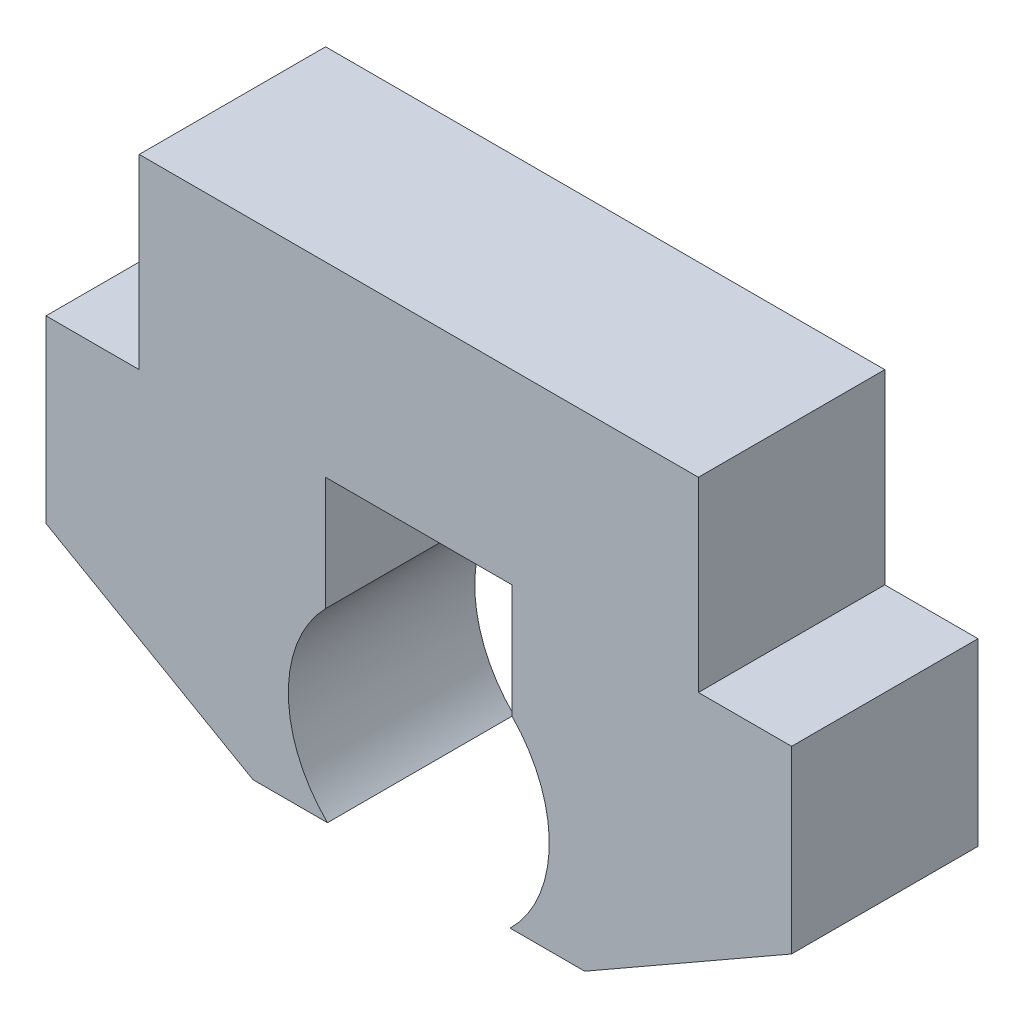
SolidWorks part; units mm, degrees
ref_plane "Спереди" through (0, 0, 0) normal (0, 0, 1) x (1, 0, 0)
ref_plane "Сверху" through (0, 0, 0) normal (0, 1, 0) x (1, 0, 0)
ref_plane "Справа" through (0, 0, 0) normal (1, 0, 0) x (0, 0, -1)
sketch "Sketch1" plane through (0, 0, 0) normal (0, 0, 1) x (1, 0, 0)
  line L0 (0, 8.8246) -> (20, 8.8246) construction
  line L1 (5.5505, 0.8246) -> (7.5505, 0.8246)
  line L2 (0, 4) -> (0, 8.8246)
  line L4 (20, 4) -> (20, 8.8246)
  line L5 (10, 0.8246) -> (10, 14.8323) construction
  line L6 (0, 4) -> (5.5505, 0.8246)
  line L7 (20, 4) -> (14.4495, 0.8246)
  line L8 (12.4495, 0.8246) -> (14.4495, 0.8246)
  line L9 (0, 4) -> (20, 4) construction
  line L12 (7.5, 8.8246) -> (12.5, 8.8246)
  line L14 (7.5, 8.8246) -> (7.5, 5.7741)
  line L15 (12.5, 8.8246) -> (12.5, 5.7741)
  line L16 (10, 13.8246) -> (17.5, 13.8246)
  line L17 (2.5, 8.8246) -> (2.5, 13.8246)
  line L18 (17.5, 8.8246) -> (17.5, 13.8246)
  line L19 (2.5, 13.8246) -> (10, 13.8246)
  line L20 (2.5, 8.8246) -> (0, 8.8246)
  line L21 (17.5, 8.8246) -> (20, 8.8246)
  arc A0 (12.4495, 0.8246) -> (12.5, 5.7741) centre (10, 3.3246) ccw
  arc A1 (7.5, 5.7741) -> (7.5505, 0.8246) centre (10, 3.3246) ccw
  point P7 (0, 4)
  point P16 (7.5505, 0.8246)
  point P17 (12.4495, 0.8246)
  dimension "D5" = 7
  dimension "D1" = 5
  dimension "D2" = 2.5
  dimension "D3" = 2.5
  dimension "D6" = 2.5
  dimension "D7" = 2
  dimension "D8" = 2
extrude "Boss-Extrude1" add sketch "Sketch1" along normal blind 5
